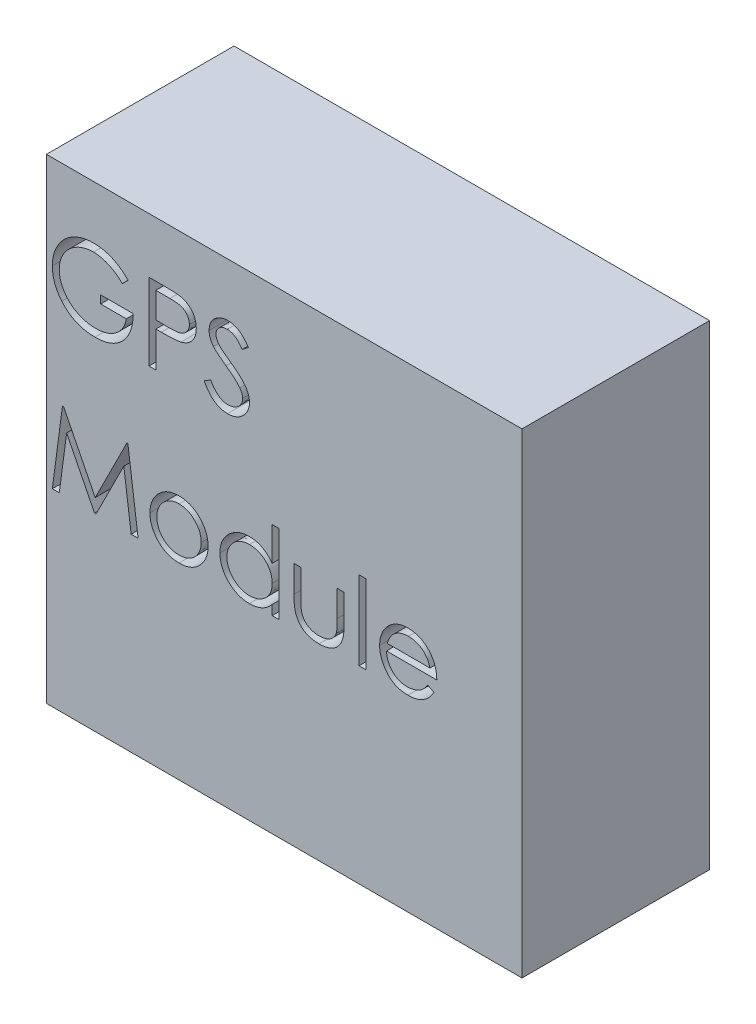
SolidWorks part; units mm, degrees
ref_plane "Front Plane" through (0, 0, 0) normal (0, 0, 1) x (1, 0, 0)
ref_plane "Top Plane" through (0, 0, 0) normal (0, 1, 0) x (1, 0, 0)
ref_plane "Right Plane" through (0, 0, 0) normal (1, 0, 0) x (0, 0, -1)
sketch "Sketch1" plane through (0, 0, 0) normal (0, 0, 1) x (1, 0, 0)
  line L1 (-9, 9) -> (9, 9)
  line L2 (-9, 9) -> (-9, -9)
  line L3 (-9, -9) -> (9, -9)
  line L4 (9, 9) -> (9, -9)
  line L5 (-9, 9) -> (9, -9) construction
  line L6 (-9, -9) -> (9, 9) construction
  point P0 (0, 0)
  dimension "D1" = 18
  dimension "D2" = 18
extrude "Boss-Extrude1" add sketch "Sketch1" along normal blind 7.1
sketch "Sketch2" plane through (0, 0, 7.1) normal (0, 0, 1) x (1, 0, 0)
  line L0 (-9, 4) -> (9, 4) construction
  line L3 (-9, 9) -> (-9, -9) construction
  line L4 (9, -9) -> (9, 9) construction
  line L5 (9, 9) -> (-9, 9) construction
  text T0 "GPS\r\nModule" font "Century Gothic" height in points 11
  dimension "D1" = 5
extrude "Cut-Extrude1" cut sketch "Sketch2" against normal blind 2
